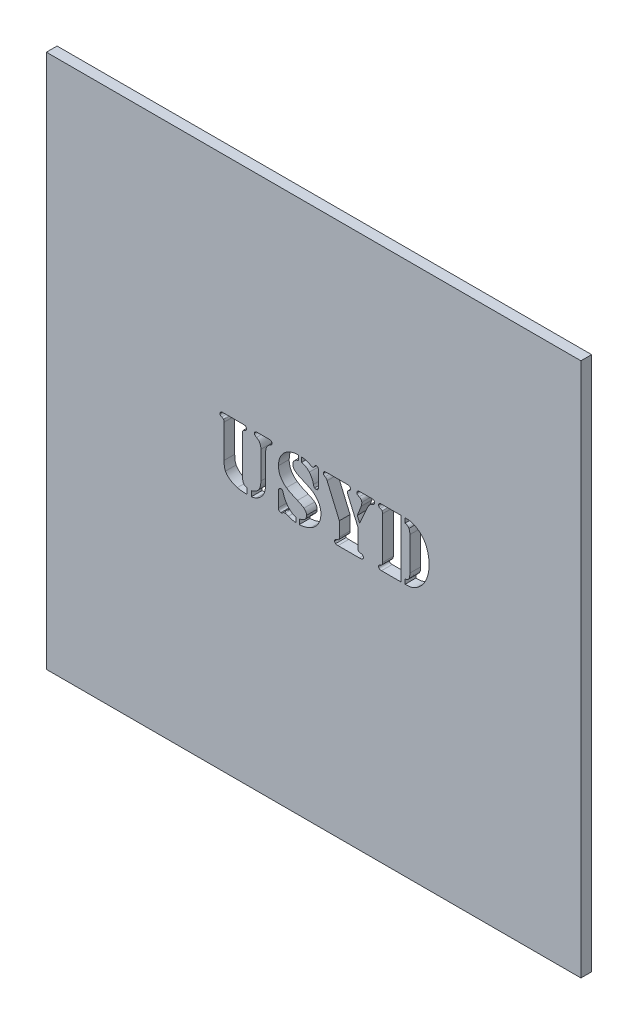
SolidWorks part; units mm, degrees
ref_plane "前视基准面" through (0, 0, 0) normal (0, 0, 1) x (1, 0, 0)
ref_plane "上视基准面" through (0, 0, 0) normal (0, 1, 0) x (1, 0, 0)
ref_plane "右视基准面" through (0, 0, 0) normal (1, 0, 0) x (0, 0, -1)
sketch "草图2" plane through (0, 0, 0) normal (0, 0, 1) x (1, 0, 0)
  line L1 (0, 0) -> (100, 0)
  line L2 (0, 0) -> (0, -100)
  line L7 (0, -100) -> (100, -100)
  line L8 (100, 0) -> (100, -100)
extrude "凸台-拉伸2" add sketch "草图2" along normal blind 2 contours L1 L8 L7 L2
sketch "草图5" plane through (0, 0, 2) normal (0, 0, 1) x (1, 0, 0)
  text T0 "USYD" font "Stencil" height in points 42
extrude "切除-拉伸1" cut sketch "草图5" against normal blind 2
